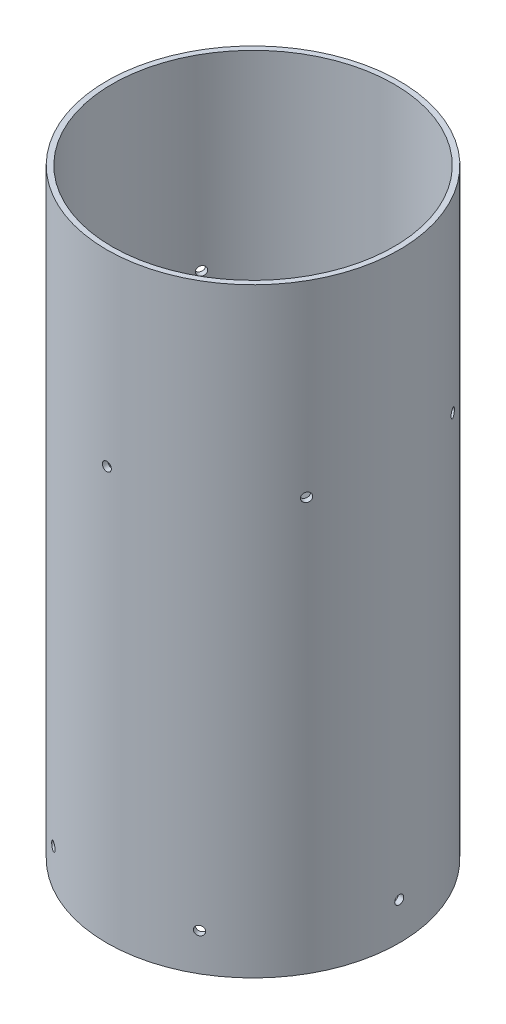
SolidWorks part; units mm, degrees
ref_plane "Front Plane" through (0, 0, 0) normal (0, 0, 1) x (1, 0, 0)
ref_plane "Top Plane" through (0, 0, 0) normal (0, 1, 0) x (1, 0, 0)
ref_plane "Right Plane" through (0, 0, 0) normal (1, 0, 0) x (0, 0, -1)
sketch "Sketch1" plane through (0, 0, 0) normal (0, 1, 0) x (1, 0, 0)
  circle A0 centre (0, 0) radius 47.6885
  circle A1 centre (0, 0) radius 49.5046
  dimension "D1" = 99.0092
  dimension "D2" = 95.377
extrude "Boss-Extrude1" add sketch "Sketch1" along normal blind 203.2
sketch "Sketch2" plane through (0, 0, 0) normal (0, 0, 1) x (1, 0, 0)
  line L0 (0, 203.2) -> (0, 141.224)
  line L1 (49.5046, 203.2) -> (-49.5046, 203.2) construction
  circle A0 centre (0, 139.7) radius 1.524
  point P7 (0, 0)
  dimension "D2" = 3.048
  dimension "D1" = 61.976
  dimension "D3" = 63.5
extrude "Cut-Extrude1" cut sketch "Sketch2" against normal blind 81.534 contours A0
pattern_circular "CirPattern1" count 6 over 360 about axis through (0, 203.2, 0) along (0, -1, 0) of "Cut-Extrude1"
sketch "Sketch3" plane through (0, 0, 0) normal (1, 0, 0) x (0, 0, -1)
  line L0 (0, 0) -> (0, 12.7) construction
  line L1 (-49.5046, 0) -> (49.5046, 0) construction
  circle A0 centre (0, 12.7) radius 1.524
  dimension "D1" = 12.7
  dimension "D2" = 3.048
extrude "Cut-Extrude2" cut sketch "Sketch3" against normal blind 81.534
pattern_circular "CirPattern2" count 6 over 360 about axis through (0, 203.2, 0) along (0, -1, 0) of "Cut-Extrude2"
